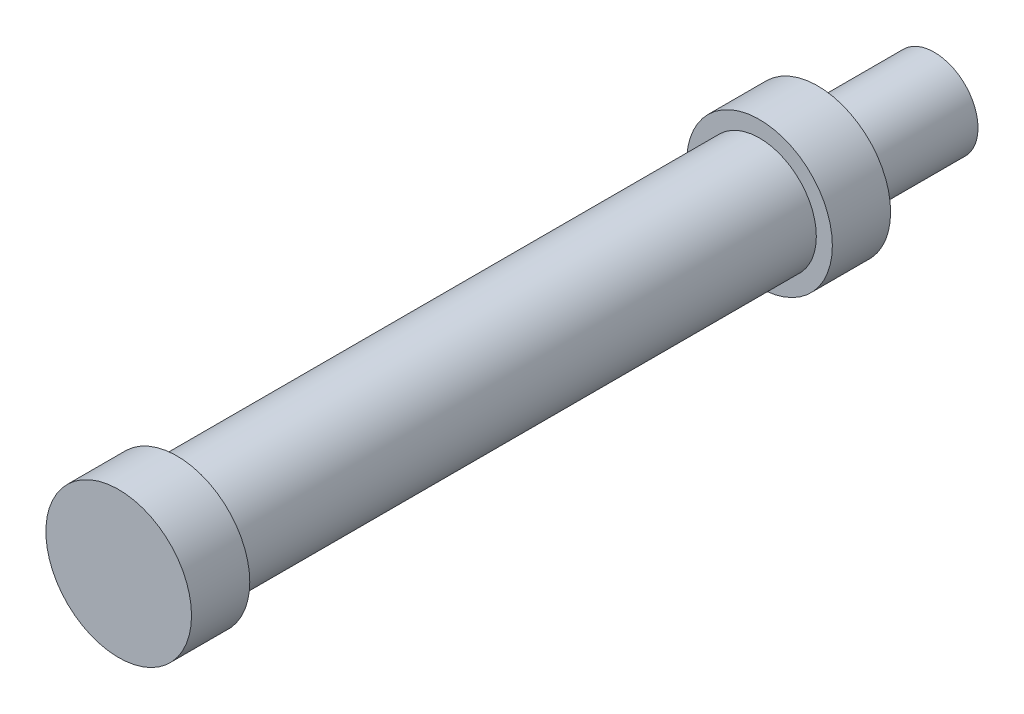
SolidWorks part; units mm, degrees
ref_plane "Front Plane" through (0, 0, 0) normal (0, 0, 1) x (1, 0, 0)
ref_plane "Top Plane" through (0, 0, 0) normal (0, 1, 0) x (1, 0, 0)
ref_plane "Right Plane" through (0, 0, 0) normal (1, 0, 0) x (0, 0, -1)
sketch "Sketch1" plane through (0, 0, 0) normal (0, 0, 1) x (1, 0, 0)
  circle A0 centre (0, 0) radius 1.5
  dimension "D1" = 3
extrude "Boss-Extrude1" add sketch "Sketch1" along normal blind 4
sketch "Sketch2" plane through (0, 0, 4) normal (0, 0, 1) x (1, 0, 0)
  circle A0 centre (0, 0) radius 2.5
  dimension "D1" = 5
extrude "Boss-Extrude2" add sketch "Sketch2" along normal blind 2
sketch "Sketch3" plane through (0, 0, 6) normal (0, 0, 1) x (1, 0, 0)
  circle A0 centre (0, 0) radius 1.95
  dimension "D1" = 3.9
extrude "Boss-Extrude3" add sketch "Sketch3" along normal blind 20
sketch "Sketch4" plane through (0, 0, 26) normal (0, 0, 1) x (1, 0, 0)
  circle A0 centre (0, 0) radius 2.5
extrude "Boss-Extrude4" add sketch "Sketch4" along normal blind 2
